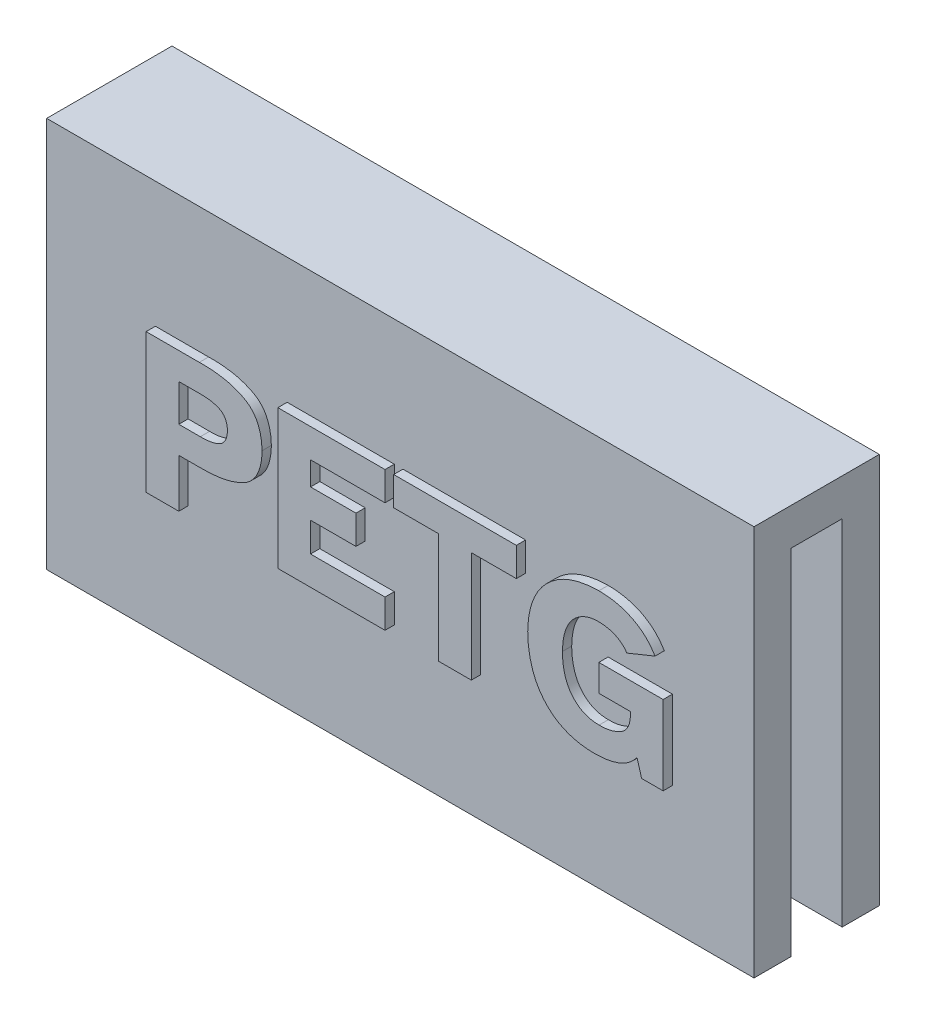
SolidWorks part; units mm, degrees
ref_plane "Front Plane" through (0, 0, 0) normal (0, 0, 1) x (1, 0, 0)
ref_plane "Top Plane" through (0, 0, 0) normal (0, 1, 0) x (1, 0, 0)
ref_plane "Right Plane" through (0, 0, 0) normal (1, 0, 0) x (0, 0, -1)
sketch "Sketch1" plane through (0, 0, 0) normal (1, 0, 0) x (0, 0, -1)
  line L0 (0, 0) -> (0, 42.1)
  line L1 (0, 42.1) -> (13.5, 42.1)
  line L2 (13.5, 42.1) -> (13.5, 0)
  line L3 (13.5, 0) -> (9.5, 0)
  line L4 (9.5, 0) -> (9.5, 38.1)
  line L5 (9.5, 38.1) -> (4, 38.1)
  line L6 (4, 38.1) -> (4, 0)
  line L7 (4, 0) -> (0, 0)
  line L8 (4, 38.1) -> (4, 42.1) construction
  dimension "D1" = 38.1
  dimension "D2" = 4
  dimension "D3" = 5.5
extrude "Boss-Extrude1" add sketch "Sketch1" along normal mid plane 76.2 contours L1 L2 L3 L4 L5 L6 L7 L0
sketch "Sketch2" plane through (0, 0, 0) normal (0, 0, 1) x (1, 0, 0)
  line L0 (-38.1, 13.55) -> (38.1, 13.55) construction
  line L1 (-38.1, 0) -> (-38.1, 42.1) construction
  line L2 (38.1, 0) -> (38.1, 42.1) construction
  line L3 (-38.1, 21.05) -> (49961.9, 21.05) construction
  line L4 (-38.1, 28.55) -> (38.1, 28.55) construction
  line L5 (-38.1, 28.55) -> (-38.1, 13.55) construction
  text T0 "<b>PETG</b>" font "Atkinson Hyperlegible" height 15
  point P9 (-38.1, 21.05)
  point P12 (-38.1, 21.05)
  point P21 (33.1, 44.9173)
  dimension "D1" = 15
extrude "Boss-Extrude3" add sketch "Sketch2" along normal mid plane 2
